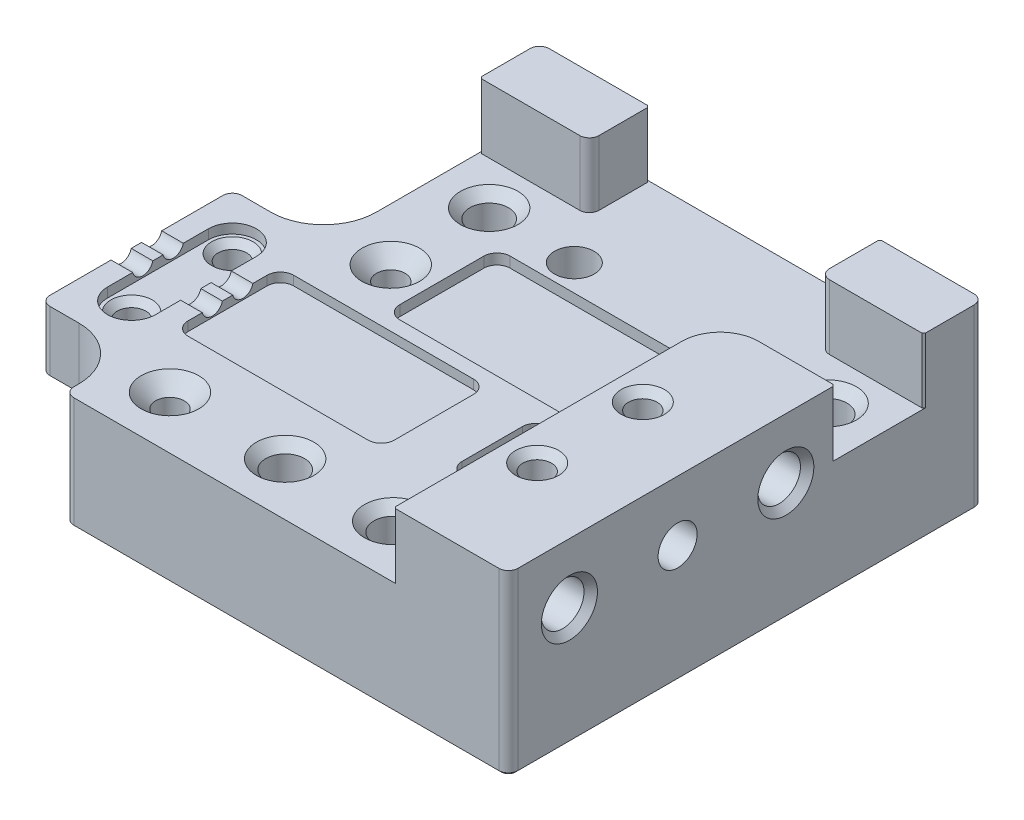
SolidWorks part; units mm, degrees
material "7075-T6 (SN)"
ref_plane "Front Plane" through (0, 0, 0) normal (0, 0, 1) x (1, 0, 0)
ref_plane "Top Plane" through (0, 0, 0) normal (0, 1, 0) x (1, 0, 0)
ref_plane "Right Plane" through (0, 0, 0) normal (1, 0, 0) x (0, 0, -1)
ref_plane "Plane3" through (0, 0, -0.635) normal (0, 0, 1) x (1, 0, 0)
sketch "Sketch1" plane through (0, 0, 0) normal (0, 1, 0) x (1, 0, 0)
  line L0 (-8.8998, 11.8508) -> (-8.8998, -3.525) construction
  line L1 (-12.6998, 13) -> (9.6002, 13)
  line L3 (-12.6998, -6.8) -> (9.6002, -6.8)
  line L5 (9.6002, -6.8) -> (9.6002, 13)
  line L7 (-12.6998, 13) -> (-12.6998, -6.8)
  circle A0 centre (2.54, 0) radius 1.27 construction
  point P2 (-1.5498, 13)
  point P4 (0.4752, 13)
  point P9 (-8.8998, 13)
  dimension "D5" = 2.54
  dimension "D1" = 2.54
  dimension "D2" = 22.3
  dimension "D3" = 6.8
  dimension "D4" = 19.8
  dimension "D6" = 1.5498
  dimension "D7" = 9.6002
  dimension "D8" = 9.125
  dimension "D9" = 3.8
  dimension "D10" = 18.5
  dimension "D11" = 13
extrude "Boss-Extrude1" add sketch "Sketch1" along normal blind 7.4
sketch "Sketch11" plane through (0, 7.4, 0) normal (0, 1, 0) x (1, 0, 0)
  line L0 (4.825, -17.1499) -> (4.825, 5.2)
  line L1 (6.425, 6.8) -> (15.9178, 6.8)
  line L2 (15.9178, 6.8) -> (15.9178, 10.5)
  line L3 (15.9178, 10.5) -> (5.2758, 10.5)
  line L4 (4.825, -17.1499) -> (-17.0227, -17.1499)
  line L5 (-12.6998, 13) -> (9.6002, 13) construction
  line L6 (-13.9236, -7.02) -> (-13.9236, 2.956)
  line L7 (-17.0227, 3.556) -> (-17.0227, 10.5)
  line L8 (-14.5236, 3.556) -> (-17.0227, 3.556)
  line L9 (9.6002, -6.8) -> (9.6002, 13) construction
  line L10 (-12.6998, -6.8) -> (9.6002, -6.8) construction
  line L11 (-14.5236, -7.62) -> (-17.0227, -7.62)
  line L12 (-17.0227, -7.62) -> (-17.0227, -17.1499)
  line L16 (5.2758, 10.5) -> (5.2758, 15.1195)
  line L17 (5.2758, 15.1195) -> (-4.3254, 15.1195)
  line L18 (-4.3254, 15.1195) -> (-4.3254, 10.5)
  line L19 (-4.3254, 10.5) -> (-17.0227, 10.5)
  arc A0 (6.425, 6.8) -> (4.825, 5.2) centre (6.425, 5.2) ccw
  arc A1 (-13.9236, 2.956) -> (-14.5236, 3.556) centre (-14.5236, 2.956) ccw
  arc A3 (-14.5236, -7.62) -> (-13.9236, -7.02) centre (-14.5236, -7.02) ccw
  point P34 (0.4752, 15.1195)
  dimension "D5" = 13.6
  dimension "D16" = 0.6
  dimension "D2" = 2.5
  dimension "D10" = 1.6
  dimension "D3" = 6.8
  dimension "D4" = 4.825
  dimension "D6" = 7.62
  dimension "D7" = 3.556
  dimension "D8" = 13.9236
  dimension "D9" = 4.7752
  dimension "D12" = 10.5
  dimension "D13" = 9.6012
extrude "Cut-Extrude8" cut sketch "Sketch11" against normal offset from surface (2.7 mm away) 4.7 up to face at (-1.5498, 0, -3.1)
sketch "Sketch9" plane through (0, 4.7, 0) normal (0, 1, 0) x (1, 0, 0)
  line L1 (-18.501, 4) -> (-8.8998, 4)
  line L3 (-18.501, 20.4901) -> (-8.8998, 20.4901)
  line L4 (-8.8998, 4) -> (-8.8998, 20.4901)
  line L6 (-18.501, 20.4901) -> (-18.501, 4)
  line L7 (-17.5459, -4) -> (-8.8998, -4)
  line L8 (-17.5459, -4) -> (-17.5459, -11.2983)
  line L9 (-17.5459, -11.2983) -> (-8.8998, -11.2983)
  line L10 (-8.8998, -4) -> (-8.8998, -11.2983)
  dimension "D1" = 4
  dimension "D2" = 4
  dimension "D5" = 9.6012
extrude "Cut-Extrude6" cut sketch "Sketch9" against normal through all and the other way through all
sketch "Sketch10" plane through (0, 4.7, 0) normal (0, 1, 0) x (1, 0, 0)
  line L0 (9.6002, -6.8) -> (9.6002, 13) construction
  line L1 (-10.3998, 7.7247) -> (-9.8998, 7.7247) construction
  line L2 (-11.3998, 6.7247) -> (-11.3998, 5.0535) construction
  line L3 (-10.3998, 4.0535) -> (-9.8998, 4.0535) construction
  line L4 (-8.8998, 6.7247) -> (-8.8998, 5.0535) construction
  line L5 (-7.2648, -5.5) -> (5.9652, -5.5)
  line L6 (6.6002, -4.865) -> (6.6002, -3.935)
  line L7 (5.9652, -3.3) -> (-7.2648, -3.3)
  line L8 (-7.8998, -3.935) -> (-7.8998, -4.865)
  line L9 (-12.6998, -6.8) -> (9.6002, -6.8) construction
  arc A0 (-9.8998, 4.0535) -> (-8.8998, 5.0535) centre (-9.8998, 5.0535) ccw construction
  arc A1 (-11.3998, 5.0535) -> (-10.3998, 4.0535) centre (-10.3998, 5.0535) ccw construction
  arc A2 (-7.2648, -3.3) -> (-7.8998, -3.935) centre (-7.2648, -3.935) ccw
  arc A3 (6.6002, -3.935) -> (5.9652, -3.3) centre (5.9652, -3.935) ccw
  arc A4 (-7.2648, -5.5) -> (-7.8998, -4.865) centre (-7.2648, -4.865) cw
  arc A5 (5.9652, -5.5) -> (6.6002, -4.865) centre (5.9652, -4.865) ccw
  arc A6 (-10.3998, 7.7247) -> (-11.3998, 6.7247) centre (-10.3998, 6.7247) ccw construction
  arc A7 (-9.8998, 7.7247) -> (-8.8998, 6.7247) centre (-9.8998, 6.7247) cw construction
  point P4 (6.6002, -4.4)
  dimension "D2" = 1
  dimension "D3" = 0.635
  dimension "D5" = 2.2
  dimension "D7" = 1
  dimension "D1" = 2.5
  dimension "D4" = 4.4
  dimension "D6" = 3
  dimension "D8" = 1
  dimension "D9" = 2.4
extrude "Cut-Extrude7" [suppressed] cut sketch "Sketch10" against normal blind 0.38
sketch "Sketch4" plane through (0, 4.7, 0) normal (0, 1, 0) x (1, 0, 0)
  line L0 (4.825, -17.1499) -> (4.825, 5.2) construction
  line L2 (-5.075, 6.85) -> (-5.075, 3.35)
  line L3 (-4.525, 2.8) -> (4.275, 2.8)
  line L4 (4.825, 6.85) -> (4.825, 3.35)
  line L8 (-4.525, 7.4) -> (4.275, 7.4)
  arc A0 (-4.525, 7.4) -> (-5.075, 6.85) centre (-4.525, 6.85) ccw
  arc A1 (4.275, 7.4) -> (4.825, 6.85) centre (4.275, 6.85) cw
  arc A2 (4.275, 2.8) -> (4.825, 3.35) centre (4.275, 3.35) ccw
  arc A3 (-5.075, 3.35) -> (-4.525, 2.8) centre (-4.525, 3.35) ccw
  point P12 (-0.125, 2.8)
  dimension "D1" = 0.55
  dimension "D5" = 4.3498
  dimension "D2" = 7.4
  dimension "D3" = 9.9
  dimension "D6" = 4.6
  dimension "D7" = 5.5502
extrude "Cut-Extrude2" cut sketch "Sketch4" against normal blind 0.4364
sketch "Sketch5" plane through (0, 4.7, 0) normal (0, 1, 0) x (1, 0, 0)
  line L1 (-8.35, 2.2) -> (-0.85, 2.2)
  line L2 (-8.9, 1.65) -> (-8.9, -1.65)
  line L3 (-8.35, -2.2) -> (-0.85, -2.2)
  line L4 (-0.3, 1.65) -> (-0.3, -1.65)
  line L6 (-12.6998, 13) -> (-12.6998, -6.8) construction
  arc A0 (-0.85, 2.2) -> (-0.3, 1.65) centre (-0.85, 1.65) cw
  arc A1 (-0.85, -2.2) -> (-0.3, -1.65) centre (-0.85, -1.65) ccw
  arc A2 (-8.35, 2.2) -> (-8.9, 1.65) centre (-8.35, 1.65) ccw
  arc A3 (-8.9, -1.65) -> (-8.35, -2.2) centre (-8.35, -1.65) ccw
  point P8 (-0.3, 0)
  dimension "D1" = 0.55
  dimension "D5" = 8.6
  dimension "D2" = 4.4
  dimension "D3" = 0.3
  dimension "D4" = 3.7998
extrude "Cut-Extrude3" cut sketch "Sketch5" against normal blind 0.387
sketch "Sketch6" plane through (0, 4.7, 0) normal (0, 1, 0) x (1, 0, 0)
  line L0 (9.6002, -6.8) -> (9.6002, 13) construction
  line L1 (2.4286, 2.0534) -> (4.275, 2.0534)
  line L2 (1.8786, 1.5034) -> (1.8786, -1.0034)
  line L3 (2.4286, -1.5534) -> (4.275, -1.5534)
  line L4 (4.825, 1.5034) -> (4.825, -1.0034)
  arc A0 (1.8786, -1.0034) -> (2.4286, -1.5534) centre (2.4286, -1.0034) ccw
  arc A1 (2.4286, 2.0534) -> (1.8786, 1.5034) centre (2.4286, 1.5034) ccw
  arc A2 (4.275, 2.0534) -> (4.825, 1.5034) centre (4.275, 1.5034) cw
  arc A3 (4.275, -1.5534) -> (4.825, -1.0034) centre (4.275, -1.0034) ccw
  point P10 (1.8786, 0.25)
  dimension "D1" = 0.55
  dimension "D2" = 1.8786
  dimension "D3" = 3.6068
  dimension "D4" = 2.9464
  dimension "D5" = 4.7752
  dimension "D6" = 0.25
extrude "Cut-Extrude4" cut sketch "Sketch6" against normal blind 0.387
sketch "Sketch41" plane through (-12.6998, 0, 0) normal (-1, 0, 0) x (0, 0, 1)
  line L0 (6.35, 5.5351) -> (-6.2047, 5.5351)
  line L1 (-6.2047, 5.5351) -> (-6.2047, 4.7508)
  line L2 (-6.2047, 4.7508) -> (-1.0668, 4.7508)
  line L3 (-0.2032, 4.7508) -> (0.2032, 4.7508)
  line L4 (1.0668, 4.7508) -> (6.35, 4.7508)
  line L5 (6.35, 4.7508) -> (6.35, 5.5351)
  line L6 (1.65, 4.7) -> (-1.65, 4.7) construction
  arc A0 (-1.0668, 4.7508) -> (-0.2032, 4.7508) centre (-0.635, 4.7508) ccw
  arc A1 (0.2032, 4.7508) -> (1.0668, 4.7508) centre (0.635, 4.7508) ccw
  point P5 (0, 4.7508)
  dimension "D2" = 0.4318
  dimension "D1" = 0.0508
  dimension "D3" = 1.27
  dimension "D4" = 6.35
extrude "Cut-Extrude11" [suppressed] cut sketch "Sketch41" against normal blind 3.2512
sketch "Sketch43" plane through (0, 0, -0.635) normal (0, 0, 1) x (1, 0, 0)
  line L0 (-14.3154, 4.3682) -> (-8.4998, 4.3682)
  line L1 (-8.068, 4.8) -> (-14.3154, 4.8)
  line L2 (-14.3154, 4.8) -> (-14.3154, 4.3682)
  line L3 (-14.3154, 4.8) -> (-15.6716, 4.8) construction
  line L4 (-8.8998, 4.7) -> (4.825, 4.7) construction
  line L5 (-12.6998, 4.7) -> (-12.6998, 0) construction
  arc A0 (-8.4998, 4.3682) -> (-8.068, 4.8) centre (-8.4998, 4.8) ccw
  dimension "D1" = 0.8636
  dimension "D2" = 0.1
  dimension "D3" = 4.2
revolve "CR-00 Input Coax Revolve" cut sketch "Sketch43" angle 360 about L3
mirror "MI-00 Input Coax Mirror" about plane through (0, 0, 0) normal (0, 0, 1) of "CR-00 Input Coax Revolve"
ref_plane "PL-01 Output Plane" through (0, 4.9, 0) normal (0, 1, 0) x (-1, 0, 0)
sketch "Sketch12" plane through (0, 4.9, 0) normal (0, 1, 0) x (-1, 0, 0)
  line L0 (-4.7518, -0.25) -> (-11.1969, -0.25)
  line L1 (-11.1969, -0.25) -> (-11.1969, -1.012)
  line L2 (-11.1969, -1.012) -> (-10.1969, -1.012)
  line L3 (-10.1969, -1.012) -> (-10.1969, -0.9485)
  line L4 (-10.1969, -0.9485) -> (-9.7999, -0.9485)
  line L5 (-9.7999, -0.9485) -> (-9.7999, -1.0628)
  line L6 (-9.7999, -1.0628) -> (-4.7518, -1.0628)
  line L7 (-4.7518, -1.0628) -> (-4.7518, -0.25)
  line L8 (-11.1969, -0.25) -> (-13.9436, -0.25) construction
  line L9 (-9.6002, 6.8) -> (-9.6002, -13) construction
  point P2 (-11.1969, -1.012)
  point P10 (-9.6002, -4.7585)
  point P11 (-9.6002, 4.2585)
  dimension "D1" = 1.6256
  dimension "D2" = 1.397
  dimension "D3" = 1.524
  dimension "D4" = 1
  dimension "D5" = 1.397
  dimension "D6" = 9.017
  dimension "D7" = 0.25
revolve "CR-00 Output Hole & Sketch" cut sketch "Sketch12" angle 360 about L8
sketch "Sketch46" plane through (0, 4.7, 0) normal (0, 1, 0) x (1, 0, 0)
  line L0 (-9.7998, -2.1) -> (-9.7998, 2.1)
  line L1 (-11.7998, 2.1) -> (-11.7998, -2.1)
  line L2 (-12.6998, 13) -> (-12.6998, -6.8) construction
  arc A0 (-9.7998, 2.1) -> (-11.7998, 2.1) centre (-10.7998, 2.1) ccw
  arc A1 (-11.7998, -2.1) -> (-9.7998, -2.1) centre (-10.7998, -2.1) ccw
  point P5 (-9.7998, 0)
  dimension "D1" = 2
  dimension "D2" = 4.2
  dimension "D3" = 1.9
extrude "CE-00 Clamp Relief" cut sketch "Sketch46" against normal blind 0.4
sketch "Sketch50" plane through (0, 0, 0) normal (0, -1, 0) x (1, 0, 0)
  line L1 (-14.3377, 6.939) -> (-8.8998, 6.939)
  line L2 (-14.3377, 6.939) -> (-14.3377, -5.9047)
  line L3 (-14.3377, -5.9047) -> (-8.8998, -5.9047)
  line L4 (-8.8998, 6.939) -> (-8.8998, -5.9047)
extrude "CE-00 Clamp Undercut" cut sketch "Sketch50" against normal offset from surface (2.2 mm away) 2.5 up to face at (-3.2301, 4.7, -2.281)
sketch "Sketch53" plane through (0, 7.4, 0) normal (0, 1, 0) x (1, 0, 0)
  line L1 (4.825, -17.1499) -> (4.825, 5.2) construction
  line L2 (5.625, -10.7206) -> (5.625, -13.6808) construction
  line L3 (6.425, 6.8) -> (15.9178, 6.8) construction
  line L4 (5.625, 6.8) -> (5.625, -3.6445)
  line L6 (2.625, -6.6445) -> (2.625, -7.7206) construction
  arc A0 (2.625, -6.6445) -> (5.625, -3.6445) centre (2.625, -3.6445) ccw
  arc A2 (2.625, -7.7206) -> (5.625, -10.7206) centre (2.625, -10.7206) cw construction
  arc A3 (5.625, -13.6808) -> (2.625, -16.6808) centre (2.625, -13.6808) cw construction
  dimension "D1" = 3
  dimension "D2" = 0.8
sketch "Sketch58" plane through (0, 0, -6.8) normal (0, 0, -1) x (-1, 0, 0)
  line L0 (-6.6604, 9.1933) -> (-4.3548, 5.2)
  line L1 (-3.0703, 5.2) -> (-3.0703, 9.1933)
  line L2 (-3.0703, 9.1933) -> (-6.6604, 9.1933)
  line L4 (-4.3548, 5.2) -> (-3.0703, 5.2)
  dimension "D1" = 30
  dimension "D3" = 2.2
sweep "Cut-Sweep4" [suppressed] cut profiles "Sketch58" path "Sketch53"
hole_wizard "#0-80 Tapped Hole Clamp" positions "Sketch39" profile "Sketch40" tap size "#0-80" standard "Ansi Inch" end condition through all
sketch "Sketch39" plane through (0.0754, 4.3, -0.2606) normal (0, 1, 0) x (-1, 0, 0)
  point P0 (10.8752, 2.3606)
  point P1 (10.8752, -1.8394)
sketch "Sketch40" plane through (-10.7998, 4.3, 2.1) normal (1, 0, 0) x (0, 0, 1)
  line L0 (0, 0) -> (0, 2.1)
  line L1 (0, 2.1) -> (1, 2.1)
  line L2 (0.5956, 1.6956) -> (0.5956, 0.268)
  line L3 (0.5956, 0.268) -> (0.8636, 0)
  line L5 (0.8636, 0) -> (0, 0)
  line L6 (-0.5956, 0.268) -> (-0.8636, 0) construction
  line L7 (1, 2.1) -> (0.5956, 1.6956)
  line L8 (-1, 2.1) -> (-0.5956, 1.6956) construction
  line L11 (0, -6.35) -> (0, 107.95) construction
  dimension "Thread Major Dia." = 1.1913
  dimension "Thru Tap Drill Depth" = 2.1
  dimension "Near C'Sink Dia." = 1.7272
  dimension "Near C'Sink Angle" = 90
  dimension "Far C'Sink Dia." = 2
  dimension "Far C'Sink Angle" = 90
hole_wizard "#0 Counterbored Hole" positions "Sketch32" profile "Sketch31" legacy end condition through all
sketch "Sketch32" plane through (3.0771, 0, 3.3065) normal (0, -1, 0) x (1, 0, 0)
  line L1 (-2.6019, -14.4038) -> (-2.6019, -21.3486) construction
  line L2 (6.5231, 3.4935) -> (6.5231, -16.3065) construction
  point P0 (0.8271, -11.8065)
  point P1 (-6.0309, -11.8065)
  dimension "D1" = 6.858
  dimension "D2" = 9.125
  dimension "D3" = 8.5
sketch "Sketch31" plane through (3.9042, 0, -8.5) normal (1, 0, 0) x (0, 0, -1)
  line L0 (0, 0) -> (0, 7.4)
  line L1 (0, 7.4) -> (0.8255, 7.4)
  line L2 (0.8255, 7.4) -> (0.8255, 2)
  line L3 (0.8255, 2) -> (1.5, 2)
  line L4 (1.5, 2) -> (1.5, 0)
  line L5 (1.5, 0) -> (0, 0)
  line L6 (0, 110) -> (0, -10) construction
  dimension "Diameter" = 1.651
  dimension "Depth" = 7.4
  dimension "C-Bore Diameter" = 3
  dimension "C-Bore Depth" = 2
hole_wizard "#0-80 Tapped Hole2" positions "Sketch18" profile "Sketch17" tap size "#0-80" standard "Ansi Inch" end condition through all
sketch "Sketch18" plane through (-2.3409, 4.7, -0.6931) normal (0, 1, 0) x (-1, 0, 0)
  line L4 (10.3589, -12.3069) -> (-11.9411, -12.3069) construction
  line L6 (6.5589, -11.1577) -> (6.5589, 4.2181) construction
  line L7 (10.3589, 7.4931) -> (-11.9411, 7.4931) construction
  point P7 (4.3589, -3.9069)
  point P34 (4.3589, 5.2931)
  dimension "D2" = 2.2
  dimension "D3" = 4.6
  dimension "D4" = 4.6
  dimension "D5" = 8.4
  dimension "D9" = 2.2
  dimension "D10" = 4.6
sketch "Sketch17" plane through (-6.6998, 4.7, -4.6) normal (1, 0, 0) x (0, 0, 1)
  line L0 (0, 0) -> (0, 4.7)
  line L1 (0, 4.7) -> (1, 4.7)
  line L2 (0.5956, 4.2956) -> (0.5956, 0.6044)
  line L3 (0.5956, 0.6044) -> (1.2, 0)
  line L5 (1.2, 0) -> (0, 0)
  line L6 (-0.5956, 0.6044) -> (-1.2, 0) construction
  line L7 (1, 4.7) -> (0.5956, 4.2956)
  line L8 (-1, 4.7) -> (-0.5956, 4.2956) construction
  line L11 (0, -6.35) -> (0, 107.95) construction
  dimension "Thread Major Dia." = 1.1913
  dimension "Thru Tap Drill Depth" = 4.7
  dimension "Near C'Sink Dia." = 2.4
  dimension "Near C'Sink Angle" = 90
  dimension "Far C'Sink Dia." = 2
  dimension "Far C'Sink Angle" = 90
hole_wizard "#52 (0.0635) Diameter Hole2" positions "Sketch20" profile "Sketch19" hole size "#52" standard "Ansi Inch" end condition through all
sketch "Sketch20" plane through (-7.2056, 4.7, -8.955) normal (0, 1, 0) x (-1, 0, 0)
  line L0 (5.4942, 15.755) -> (-16.8058, 15.755) construction
  line L1 (-16.8058, 15.755) -> (-16.8058, -4.045) construction
  line L2 (1.6942, -2.8958) -> (1.6942, 12.48) construction
  point P0 (-9.8058, 13.555)
  point P1 (-5.3058, 13.555)
  dimension "D1" = 2.2
  dimension "D2" = 4.6
  dimension "D4" = 7
  dimension "D5" = 4.5
  dimension "D7" = 7
sketch "Sketch19" plane through (2.6002, 4.7, 4.6) normal (1, 0, 0) x (0, 0, 1)
  line L0 (0, 0) -> (0, 4.7)
  line L1 (0, 4.7) -> (1, 4.7)
  line L2 (0.8064, 4.5064) -> (0.8064, 0.3936)
  line L3 (0.8064, 0.3936) -> (1.2, 0)
  line L5 (1.2, 0) -> (0, 0)
  line L6 (-0.8064, 0.3936) -> (-1.2, 0) construction
  line L7 (1, 4.7) -> (0.8064, 4.5064)
  line L8 (-1, 4.7) -> (-0.8065, 4.5064) construction
  line L11 (0, -6.35) -> (0, 107.95) construction
  dimension "Thru Hole Dia." = 1.6129
  dimension "Thru Hole Depth" = 4.7
  dimension "Near C'Sink Dia." = 2.4
  dimension "Near C'Sink Angle" = 90
  dimension "Far C'Sink Dia." = 2
  dimension "Far C'Sink Angle" = 90
hole_wizard "#0 Clearance Hole2" positions "Sketch22" profile "Sketch21" hole size "#0" standard "Ansi Inch" end condition through all
sketch "Sketch22" plane through (-8.3936, 4.7, 4.6461) normal (0, 1, 0) x (-1, 0, 0)
  line L0 (4.3062, -17.6461) -> (-17.9938, -17.6461) construction
  line L1 (-17.9938, 2.1539) -> (-17.9938, -17.6461) construction
  line L2 (0.5062, -16.4969) -> (0.5062, -1.1211) construction
  point P0 (-15.7938, -13.3461)
  point P1 (-1.6938, -13.3461)
  dimension "D1" = 4.3
  dimension "D2" = 2.2
  dimension "D3" = 7.4002
  dimension "D4" = 2.2
  dimension "D5" = 8.7
  dimension "D6" = 6.6998
sketch "Sketch21" plane through (7.4002, 4.7, -8.7) normal (1, 0, 0) x (0, 0, 1)
  line L0 (0, 0) -> (0, 4.7)
  line L1 (0, 4.7) -> (1, 4.7)
  line L2 (0.8064, 4.5064) -> (0.8064, 0.3936)
  line L3 (0.8064, 0.3936) -> (1.2, 0)
  line L5 (1.2, 0) -> (0, 0)
  line L6 (-0.8064, 0.3936) -> (-1.2, 0) construction
  line L7 (1, 4.7) -> (0.8064, 4.5064)
  line L8 (-1, 4.7) -> (-0.8065, 4.5064) construction
  line L11 (0, -6.35) -> (0, 107.95) construction
  dimension "Thru Hole Dia." = 1.6129
  dimension "Thru Hole Depth" = 4.7
  dimension "Near C'Sink Dia." = 2.4
  dimension "Near C'Sink Angle" = 90
  dimension "Far C'Sink Dia." = 2
  dimension "Far C'Sink Angle" = 90
hole_wizard "#0-80 Tapped Hole7" positions "Sketch29" profile "Sketch28" tap size "#0-80" standard "Ansi Inch" end condition through all
sketch "Sketch29" plane through (-4.7954, 7.4, 16.3892) normal (0, 1, 0) x (-1, 0, 0)
  line L2 (7.9044, -9.5892) -> (-14.3956, -9.5892) construction
  line L3 (-14.3956, -9.5892) -> (-14.3956, -29.3892) construction
  point P5 (-10.9956, -14.1892)
  point P20 (-10.9956, -18.5892)
  dimension "D1" = 4.6
  dimension "D2" = 2.2
  dimension "D3" = 3.4
  dimension "D5" = 2.2
sketch "Sketch28" plane through (6.2002, 7.4, 2.2) normal (1, 0, 0) x (0, 0, 1)
  line L0 (0, 0) -> (0, 7.4)
  line L1 (0, 7.4) -> (1, 7.4)
  line L2 (0.5956, 6.9956) -> (0.5956, 0.3044)
  line L3 (0.5956, 0.3044) -> (0.9, 0)
  line L5 (0.9, 0) -> (0, 0)
  line L6 (-0.5956, 0.3044) -> (-0.9, 0) construction
  line L7 (1, 7.4) -> (0.5956, 6.9956)
  line L8 (-1, 7.4) -> (-0.5956, 6.9956) construction
  line L11 (0, -6.35) -> (0, 107.95) construction
  dimension "Thread Major Dia." = 1.1913
  dimension "Thru Tap Drill Depth" = 7.4
  dimension "Near C'Sink Dia." = 1.8
  dimension "Near C'Sink Angle" = 90
  dimension "Far C'Sink Dia." = 2
  dimension "Far C'Sink Angle" = 90
hole_wizard "#2-56 Tapped Hole1" positions "Sketch49" profile "Sketch48" tap size "#2-56" standard "Ansi Inch"
sketch "Sketch49" plane through (9.6002, 0, 0) normal (1, 0, 0) x (0, 0, -1)
  point P0 (4.7585, 4.9)
  point P1 (-4.2585, 4.9)
sketch "Sketch48" plane through (9.6002, 4.9, -4.7585) normal (0, 1, 0) x (0, 0, -1)
  line L0 (0, 0) -> (0, 4.5342)
  line L1 (0, 4.5342) -> (0.889, 4)
  line L2 (0.889, 4) -> (0.889, 0.2794)
  line L3 (0.889, 0.2794) -> (1.1684, 0)
  line L5 (1.1684, 0) -> (0, 0)
  line L6 (-0.889, 0.2794) -> (-1.1684, 0) construction
  line L10 (0, 4.5342) -> (-0.889, 4) construction
  line L11 (0, -6.35) -> (0, 107.95) construction
  dimension "Tap Drill Dia." = 1.778
  dimension "Tap Drill Depth" = 4
  dimension "Near C'Sink Dia." = 2.3368
  dimension "Near C'Sink Angle" = 90
  dimension "Drill Angle" = 118
hole_wizard "Ø1.0 (1) Diameter Hole1" positions "Sketch57" profile "Sketch56" hole size "Ø1.0" standard "Ansi Metric"
sketch "Sketch57" plane through (9.6002, 0, 0) normal (1, 0, 0) x (0, 0, -1)
  point P0 (4.7585, 4.9)
  point P1 (-4.2585, 4.9)
sketch "Sketch56" plane through (9.6002, 4.9, -4.7585) normal (0, 1, 0) x (0, 0, -1)
  line L0 (0, 0) -> (0, 5.7004)
  line L1 (0, 5.7004) -> (0.5, 5.4)
  line L2 (0.5, 5.4) -> (0.5, 0)
  line L5 (0.5, 0) -> (0, 0)
  line L10 (0, 5.7004) -> (-0.5, 5.4) construction
  line L11 (0, -6.35) -> (0, 107.95) construction
  dimension "Hole Dia." = 1
  dimension "Hole Depth" = 5.4
  dimension "Drill Angle" = 118
sketch "Sketch44" [suppressed] plane through (0, 4.604, 0) normal (0, 1, 0) x (1, 0, 0)
  line L0 (-3.5805, 5.52) -> (-6.7, 5.52)
  line L1 (-6.7, 7.8) -> (-3.5805, 7.8)
  line L2 (-3.5805, 5.52) -> (-3.5805, 7.8)
  arc A0 (-6.7, 5.52) -> (-6.7, 7.8) centre (-6.7, 6.66) cw
  dimension "D2" = 1.14
  dimension "D1" = 4.2
extrude "CE-00 Temp Sense Pocket" [suppressed] cut sketch "Sketch44" against normal up to surface (0.4064 mm away)
fillet "FL-00 Temp Sensor Fillet" [suppressed] radius 0.5
sketch "Sketch45" [suppressed] plane through (0, 4.604, 0) normal (0, 1, 0) x (1, 0, 0)
  circle A0 centre (-6.7, 6.66) radius 1
  dimension "D1" = 2
extrude "CE-00 Temp Sense Hole" [suppressed] cut sketch "Sketch45" against normal through all
sketch "Sketch30" [suppressed] plane through (0, 0, 0) normal (0, -1, 0) x (1, 0, 0)
  line L0 (8, 6.5) -> (8, -13.5) construction
  line L1 (-4.1, -11) -> (3.7, -11)
  line L2 (-5.1, -10) -> (-5.1, -8.3)
  line L3 (-4.1, -5) -> (3.557, -5)
  line L4 (4.7, -10) -> (4.7, -6.143)
  line L6 (-6.7, -7.8) -> (-5.6, -7.8)
  line L7 (-4.2951, -5.0192) -> (-6.9224, -5.5419)
  arc A0 (3.7, -11) -> (4.7, -10) centre (3.7, -10) ccw
  arc A1 (-4.1, -11) -> (-5.1, -10) centre (-4.1, -10) cw
  arc A2 (-5.6, -7.8) -> (-5.1, -8.3) centre (-5.6, -8.3) cw
  arc A3 (-4.2951, -5.0192) -> (-4.1, -5) centre (-4.1, -6) cw
  arc A5 (4.7, -6.143) -> (3.557, -5) centre (3.557, -6.143) ccw
  arc A6 (-6.9224, -5.5419) -> (-6.7, -7.8) centre (-6.7, -6.66) ccw
  point P17 (-0.2, -11)
  dimension "D1" = 1
  dimension "D2" = 5
  dimension "D4" = 1.143
  dimension "D11" = 1.14
  dimension "D6" = 0.5
  dimension "D3" = 8.2
  dimension "D5" = 9.8
  dimension "D7" = 6
extrude "CE-00 Temp Sensor Pocket" [suppressed] cut sketch "Sketch30" against normal blind 2.4
fillet "Fillet1" radius 0.4 2 edges at (-12.6998, 3.45, -4) (-12.6998, 3.45, 4)
fillet "Fillet2" radius 0.4 6 edges at (-8.8998, 3.7, -13) (9.6002, 3.7, -13) (9.6002, 3.7, 6.8) (-8.8998, 2.35, 6.8) (5.2758, 6.05, -10.5) (-4.3254, 6.05, -10.5)
fillet "Fillet3" radius 2.2 2 edges at (-8.8998, 3.45, -4) (-8.8998, 3.45, 4)
sketch "Sketch54" plane through (0, 7.4, 0) normal (0, 1, 0) x (1, 0, 0)
  line L0 (9.6002, -6.8) -> (9.6002, 13) construction
  line L1 (0.4331, 8.6354) -> (6.0002, 8.6354)
  line L2 (0.4331, 8.6354) -> (0.4331, -4.8)
  line L3 (0.4331, -4.8) -> (3.0002, -4.8)
  line L4 (6.0002, 8.6354) -> (6.0002, -1.8)
  line L5 (-12.6998, -6.8) -> (9.6002, -6.8) construction
  arc A0 (3.0002, -4.8) -> (6.0002, -1.8) centre (3.0002, -1.8) ccw
  dimension "D1" = 3
  dimension "D2" = 3.6
  dimension "D3" = 2
extrude "Cut-Extrude14" [suppressed] cut sketch "Sketch54" against normal blind 3 draft 30
fillet "Fillet5" [suppressed] radius 1.2
fillet "Fillet6" [suppressed] radius 0.05
chamfer "Chamfer A 0.10mm" distance 0.1 angle 45 8 edges at (0.3502, 0, -13) (-8.7826, 0, -12.8828) (9.483, 0, -12.8828) (-8.8998, 0, -3.1) (9.6002, 0, -3.1) (-8.7826, 0, 6.6828) (9.483, 0, 6.6828) (0.3502, 0, 6.8)
sketch "Sketch59" plane through (0, 0, 6.8) normal (0, 0, 1) x (1, 0, 0)
  line L2 (-4.8998, 1) -> (6.3791, 1) construction
  line L3 (-8.8998, 0.1) -> (-8.8998, 4.7) construction
  text T0 "SN 0001A" font "Century Gothic" height 1.6
  dimension "D1" = 1
  dimension "D2" = 4
extrude "CE-00 Serial Number" [suppressed] cut sketch "Sketch59" against normal blind 0.2
chamfer "Chamfer2" distance 0.07 angle 45 6 edges at (-4.3254, 6.05, -13) (-8.8998, 6.05, -10.5) (4.825, 6.05, 6.8) (9.6002, 6.05, -6.8) (9.6002, 6.05, -10.5) (5.2758, 6.05, -13)
